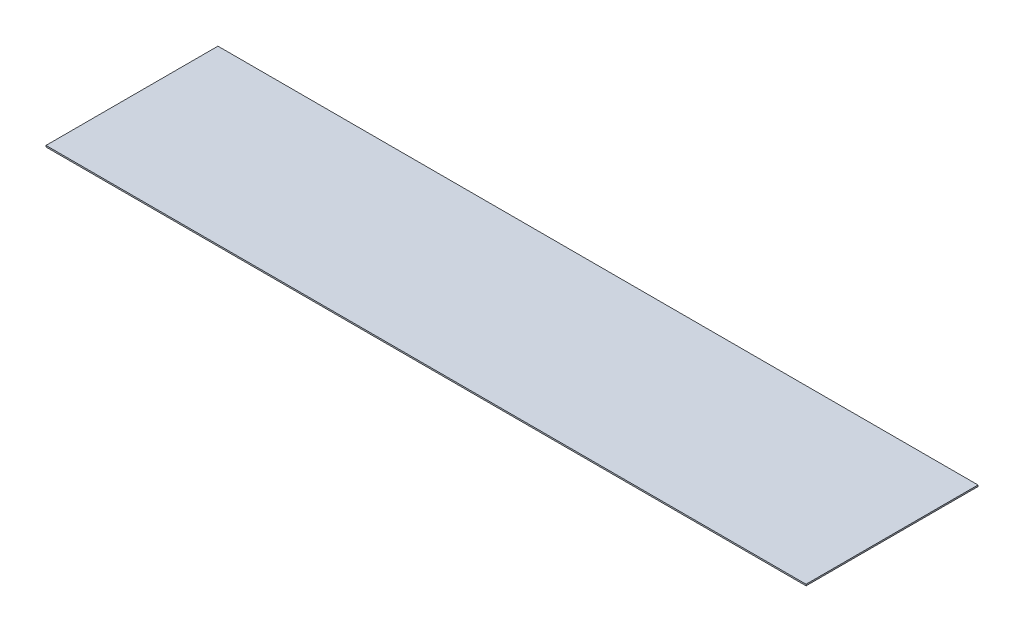
SolidWorks part; units mm, degrees
material "Natural Rubber"
ref_plane "Front" through (0, 0, 0) normal (0, 0, 1) x (1, 0, 0)
ref_plane "Top" through (0, 0, 0) normal (0, 1, 0) x (1, 0, 0)
ref_plane "Right" through (0, 0, 0) normal (1, 0, 0) x (0, 0, -1)
sketch "Sketch1" plane through (0, 0, 0) normal (0, 1, 0) x (1, 0, 0)
  line L1 (-1447.8, 825.5) -> (1447.8, 825.5)
  line L2 (-1447.8, 825.5) -> (-1447.8, -825.5)
  line L3 (-1447.8, -825.5) -> (1447.8, -825.5)
  line L4 (1447.8, 825.5) -> (1447.8, -825.5)
  line L5 (-1447.8, 825.5) -> (1447.8, -825.5) construction
  line L6 (-1447.8, -825.5) -> (1447.8, 825.5) construction
  point P0 (0, 0)
  dimension "D1" = 2895.6
  dimension "D2" = 1651
extrude "Boss-Extrude1" [suppressed] add sketch "Sketch1" along normal blind 1473.2
sketch "Sketch2" [suppressed] plane through (0, 0, 0) normal (0, -1, 0) x (1, 0, 0)
  line L0 (0, 0) -> (2162.175, 0) construction
  line L1 (1447.8, 825.5) -> (1447.8, -825.5) construction
  line L2 (1752.6, 663.575) -> (2571.75, 663.575)
  line L3 (1752.6, 663.575) -> (1752.6, -663.575)
  line L4 (1752.6, -663.575) -> (2571.75, -663.575)
  line L5 (2571.75, 663.575) -> (2571.75, -663.575)
  line L6 (1752.6, 663.575) -> (2571.75, -663.575) construction
  line L7 (1752.6, -663.575) -> (2571.75, 663.575) construction
  dimension "D1" = 1327.15
  dimension "D2" = 819.15
  dimension "D3" = 304.8
extrude "Boss-Extrude2" [suppressed] add sketch "Sketch2" against normal blind 736.6 separate body
sketch "Sketch3" plane through (0, 0, 0) normal (0, 1, 0) x (-1, 0, 0)
  line L2 (6127.75, 914.4) -> (-6127.75, 914.4)
  line L3 (6127.75, 914.4) -> (6127.75, -914.4)
  line L4 (6127.75, -914.4) -> (-6127.75, -914.4)
  line L5 (-6127.75, 914.4) -> (-6127.75, -914.4)
  line L6 (6127.75, 914.4) -> (-6127.75, -914.4) construction
  line L7 (6127.75, -914.4) -> (-6127.75, 914.4) construction
  dimension "D1" = 1828.8
  dimension "D2" = 12255.5
extrude "Boss-Extrude3" add sketch "Sketch3" along normal blind 304.8 separate body
sketch "Sketch4" plane through (0, 304.8, 0) normal (0, 1, 0) x (1, 0, 0)
  line L0 (6127.75, -914.4) -> (6127.75, 914.4) construction
  line L1 (-6737.35, 1524) -> (6737.35, 1524)
  line L2 (-6737.35, 1524) -> (-6737.35, -1524)
  line L3 (-6737.35, -1524) -> (6737.35, -1524)
  line L4 (6737.35, 1524) -> (6737.35, -1524)
  line L5 (-6737.35, 1524) -> (6737.35, -1524) construction
  line L6 (-6737.35, -1524) -> (6737.35, 1524) construction
  line L7 (-6127.75, -914.4) -> (6127.75, -914.4) construction
  point P0 (0, 0)
  dimension "D1" = 609.6
  dimension "D2" = 609.6
extrude "Boss-Extrude4" add sketch "Sketch4" along normal blind 25.4 separate body
